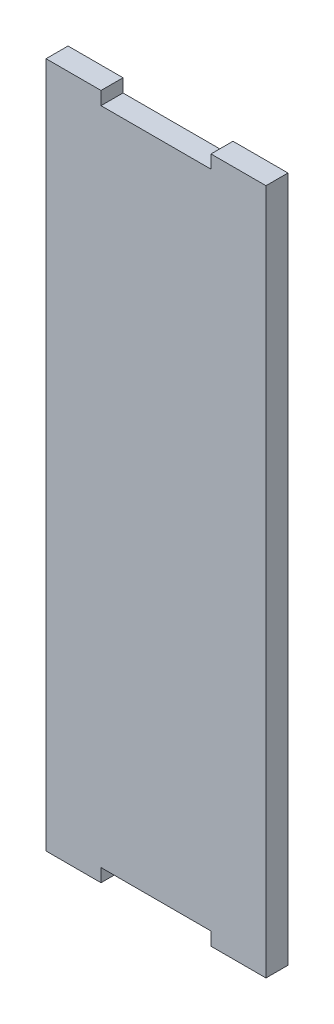
SolidWorks part; units mm, degrees
ref_plane "Front Plane" through (0, 0, 0) normal (0, 0, 1) x (1, 0, 0)
ref_plane "Top Plane" through (0, 0, 0) normal (0, 1, 0) x (1, 0, 0)
ref_plane "Right Plane" through (0, 0, 0) normal (1, 0, 0) x (0, 0, -1)
sketch "Sketch1" plane through (0, 0, 0) normal (0, 0, 1) x (1, 0, 0)
  line L1 (-25, 78) -> (25, 78)
  line L2 (-25, 78) -> (-25, -78)
  line L3 (-25, -78) -> (25, -78)
  line L4 (25, 78) -> (25, -78)
  line L5 (-25, 78) -> (25, -78) construction
  line L6 (-25, -78) -> (25, 78) construction
  point P0 (0, 0)
  dimension "D1" = 156
  dimension "D2" = 50
extrude "Boss-Extrude1" add sketch "Sketch1" along normal blind 5
sketch "Sketch2" plane through (0, 0, 5) normal (0, 0, 1) x (1, 0, 0)
  line L0 (-0.2875, 0) -> (49999.7125, 0) construction
  line L1 (0, 0) -> (0, -50000) construction
  line L2 (25, 78) -> (-25, 78) construction
  line L3 (-12.5, 78) -> (12.5, 78)
  line L4 (-12.5, 78) -> (-12.5, 75)
  line L5 (-12.5, 75) -> (12.5, 75)
  line L6 (12.5, 78) -> (12.5, 75)
  line L7 (-12.5, 78) -> (12.5, 75) construction
  line L8 (-12.5, 75) -> (12.5, 78) construction
  line L9 (-12.5, -78) -> (12.5, -78)
  line L10 (12.5, -78) -> (12.5, -75)
  line L11 (-12.5, -75) -> (12.5, -75)
  line L12 (-12.5, -78) -> (-12.5, -75)
  point P5 (0, 76.5)
  dimension "D1" = 3
  dimension "D2" = 25
extrude "Cut-Extrude1" cut sketch "Sketch2" against normal blind 20.32 and the other way blind 22.86
